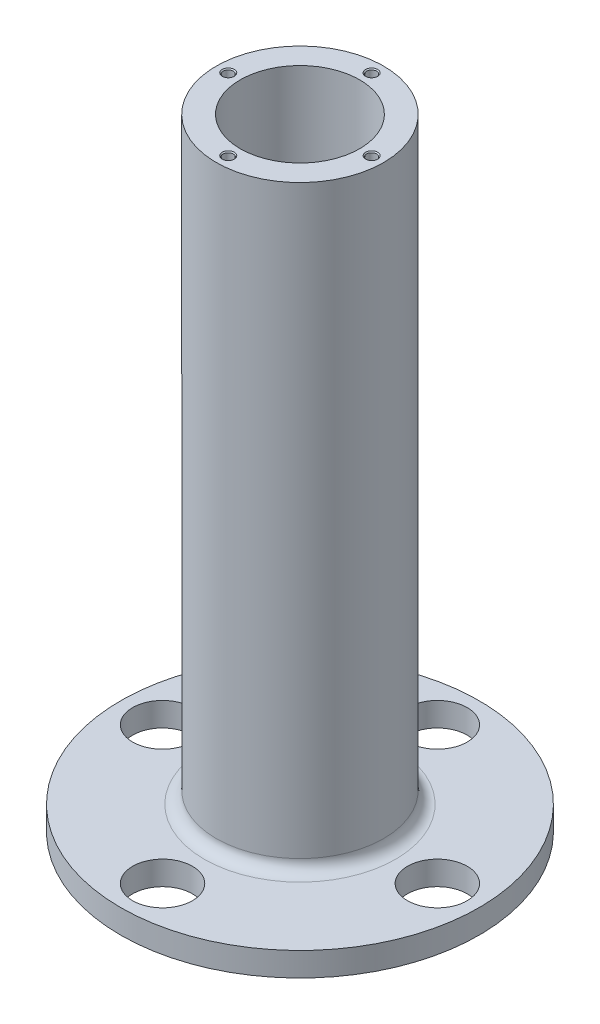
SolidWorks part; units mm, degrees
ref_plane "前视基准面" through (0, 0, 0) normal (0, 0, 1) x (1, 0, 0)
ref_plane "上视基准面" through (0, 0, 0) normal (0, 1, 0) x (1, 0, 0)
ref_plane "右视基准面" through (0, 0, 0) normal (1, 0, 0) x (0, 0, -1)
sketch "草图1" plane through (0, 0, 0) normal (0, 1, 0) x (1, 0, 0)
  circle A0 centre (0, 0) radius 75
  dimension "D1" = 150
extrude "凸台-拉伸1" add sketch "草图1" along normal blind 10
sketch "草图2" plane through (0, 10, 0) normal (0, 1, 0) x (1, 0, 0)
  circle A0 centre (0, 0) radius 25
  dimension "D1" = 50
extrude "拉伸-薄壁1" add sketch "草图2" along normal blind 250 thin
sketch "草图3" plane through (0, 10, 0) normal (0, 1, 0) x (1, 0, 0)
  circle A0 centre (0, 0) radius 57.5 construction
  point P3 (57.5, 0)
  point P7 (0, -57.5)
  point P8 (-57.5, 0)
  point P9 (0, 57.5)
  dimension "D1" = 115
  dimension "D2" = 4
hole_wizard "孔1" positions "草图3" profile "草图4" legacy end condition up to next
sketch "草图4" plane through (0, 10, -57.5) normal (1, 0, 0) x (0, 0, 1)
  line L0 (0, 0) -> (0, 10)
  line L1 (0, 10) -> (12.5, 10)
  line L2 (12.5, 10) -> (12.5, 0)
  line L3 (12.5, 0) -> (0, 0)
  line L4 (0, 110) -> (0, -10) construction
  dimension "直径" = 25
  dimension "深度" = 10
sketch "草图5" plane through (0, 260, 0) normal (0, 1, 0) x (1, 0, 0)
  circle A0 centre (0, 0) radius 30 construction
  point P3 (-30, 0)
  point P7 (0, 30)
  point P8 (30, 0)
  point P9 (0, -30)
  dimension "D1" = 60
  dimension "D2" = 4
hole_wizard "M5 螺纹孔1" positions "草图5" profile "草图7" tap size "M5" standard "GB"
sketch "草图7" plane through (0, 260, 30) normal (1, 0, 0) x (0, 0, 1)
  line L0 (0, 0) -> (0, 23.6618)
  line L1 (0, 23.6618) -> (2.1, 22.4)
  line L2 (2.1, 22.4) -> (2.1, 0.425)
  line L3 (2.1, 0.425) -> (2.525, 0)
  line L5 (2.525, 0) -> (0, 0)
  line L6 (-2.1, 0.425) -> (-2.525, 0) construction
  line L10 (0, 23.6618) -> (-2.1, 22.4) construction
  line L11 (0, -6.35) -> (0, 107.95) construction
  dimension "螺纹孔钻头直径" = 4.2
  dimension "螺纹孔钻头深度" = 22.4
  dimension "近端锥形沉头孔直径" = 5.05
  dimension "近端锥形沉头孔角度" = 90
  dimension "导头角度" = 118
cosmetic thread "孔螺纹线5" parameters "D1"=20, "D2"=5
cosmetic thread "孔螺纹线6" parameters "D1"=20, "D2"=5
cosmetic thread "孔螺纹线7" parameters "D1"=20, "D2"=5
cosmetic thread "孔螺纹线8" parameters "D1"=20, "D2"=5
fillet "圆角1" radius 5 1 edges at (35, 10, 0)
